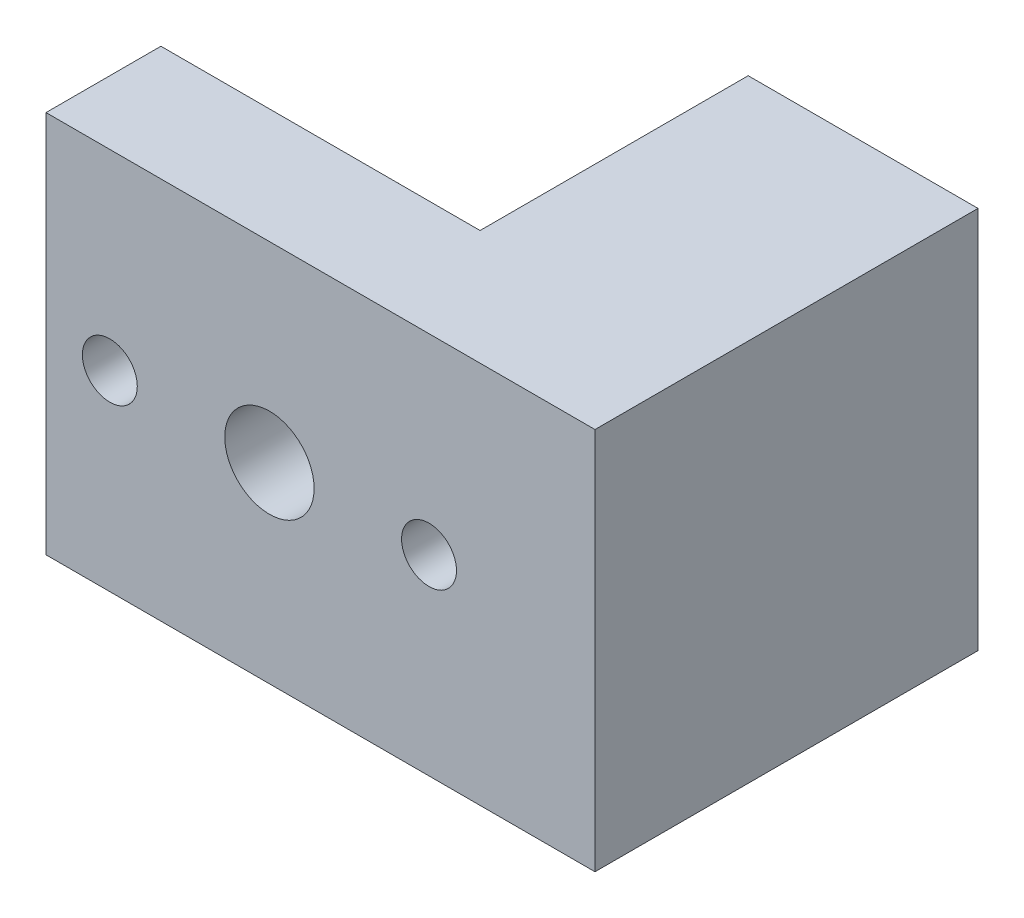
SolidWorks part; units mm, degrees
ref_plane "前视基准面" through (0, 0, 0) normal (0, 0, 1) x (1, 0, 0)
ref_plane "上视基准面" through (0, 0, 0) normal (0, 1, 0) x (1, 0, 0)
ref_plane "右视基准面" through (0, 0, 0) normal (1, 0, 0) x (0, 0, -1)
sketch "Sketch1" plane through (0, 0, 0) normal (0, 0, 1) x (1, 0, 0)
  line L0 (-332.7002, 114.6447) -> (-332.7002, -114.6447) construction
  line L1 (-332.7002, -62.5) -> (-289.7002, -62.5)
  line L2 (-332.7002, -62.5) -> (-332.7002, -32.5)
  line L3 (-332.7002, -32.5) -> (-289.7002, -32.5)
  line L4 (-289.7002, -62.5) -> (-289.7002, -32.5)
  line L5 (-307.7002, -139.1421) -> (-307.7002, 139.1421) construction
  circle A0 centre (-327.7002, -47.5) radius 2.15 construction
  circle A1 centre (-327.7002, -47.5) radius 2.15
  circle A2 centre (-315.2002, -47.5) radius 3.5
  dimension "D2" = 15
  dimension "D4" = 7
  dimension "D1" = 15
  dimension "D3" = 18
extrude "Boss-Extrude1" add sketch "Sketch1" along normal blind 9
sketch "Sketch2" plane through (0, 0, 0) normal (0, 0, -1) x (-1, 0, 0)
  line L0 (307.7002, -139.1421) -> (307.7002, 139.1421) construction
  line L1 (307.7002, -62.5) -> (289.7002, -62.5)
  line L2 (307.7002, -62.5) -> (307.7002, -32.5)
  line L3 (307.7002, -32.5) -> (289.7002, -32.5)
  line L4 (289.7002, -62.5) -> (289.7002, -32.5)
  line L5 (332.7002, -62.5) -> (289.7002, -62.5) construction
extrude "Boss-Extrude2" add sketch "Sketch2" along normal up to vertex (21 mm away)
sketch "Sketch3" plane through (0, 0, 9) normal (0, 0, 1) x (1, 0, 0)
  circle A0 centre (-302.7002, -47.5) radius 2.15
  dimension "D1" = 4.3
extrude "Cut-Extrude1" cut sketch "Sketch3" against normal through all
